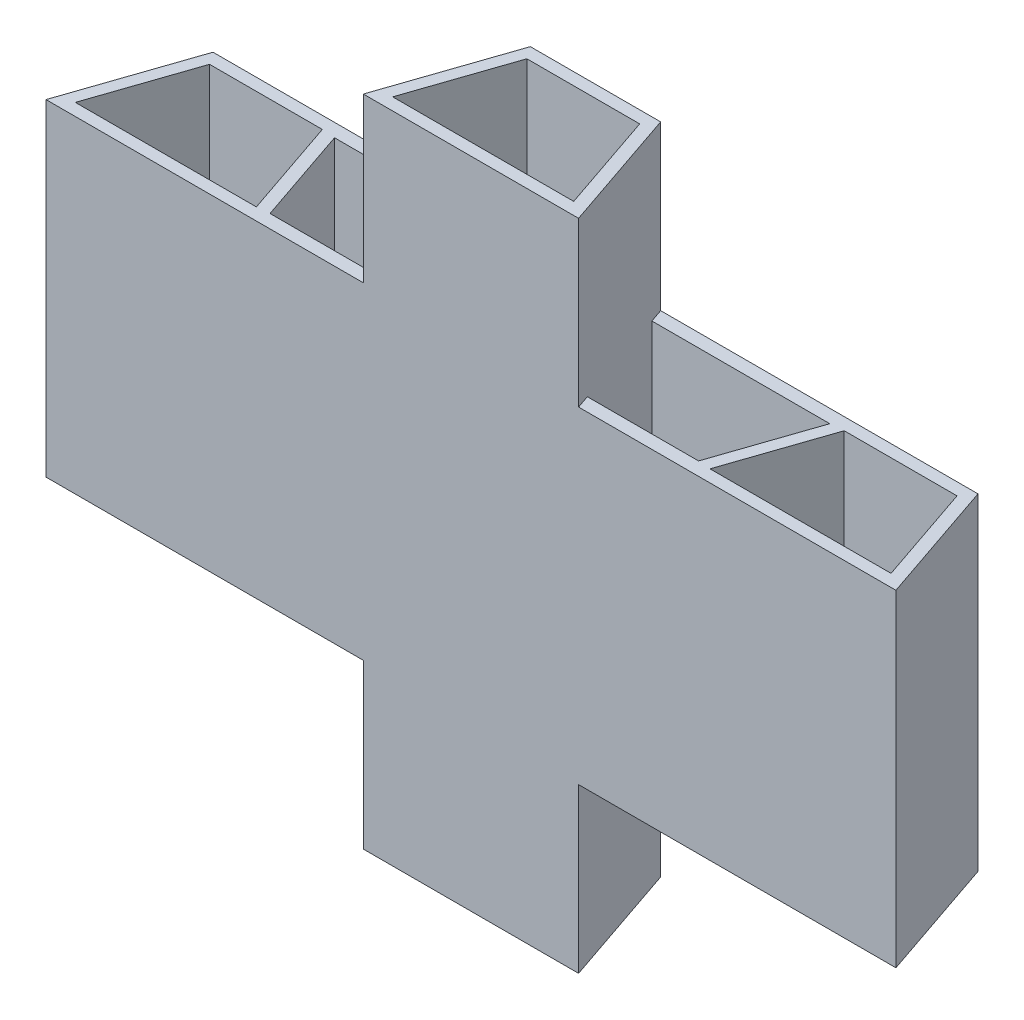
SolidWorks part; units mm, degrees
ref_plane "Front Plane" through (0, 0, 0) normal (0, 0, 1) x (1, 0, 0)
ref_plane "Top Plane" through (0, 0, 0) normal (0, 1, 0) x (1, 0, 0)
ref_plane "Right Plane" through (0, 0, 0) normal (1, 0, 0) x (0, 0, -1)
sketch "Sketch1" plane through (0, 0, 0) normal (0, 1, 0) x (1, 0, 0)
  line L0 (0, 54.8298) -> (0, -49.2445) construction
  line L1 (-104.9814, 0) -> (120.0907, 0) construction
  line L2 (-20, 3) -> (20, 3)
  line L3 (20, 3) -> (12.5, 25)
  line L4 (12.5, 25) -> (-12.5, 25)
  line L5 (-20, 3) -> (-12.5, 25)
  line L6 (15.6695, 25) -> (23.1695, 3)
  line L7 (23.1695, 3) -> (48.1695, 3)
  line L8 (48.1695, 3) -> (55.6695, 25)
  line L9 (55.6695, 25) -> (15.6695, 25)
  line L10 (-48.1695, 3) -> (-55.6695, 25)
  line L11 (-23.1695, 3) -> (-48.1695, 3)
  line L12 (-15.6695, 25) -> (-23.1695, 3)
  line L13 (-55.6695, 25) -> (-15.6695, 25)
  line L14 (58.8391, 25) -> (51.3391, 3)
  line L15 (51.3391, 3) -> (91.3391, 3)
  line L16 (91.3391, 3) -> (83.8391, 25)
  line L17 (83.8391, 25) -> (58.8391, 25)
  line L18 (-91.3391, 3) -> (-83.8391, 25)
  line L19 (-51.3391, 3) -> (-91.3391, 3)
  line L20 (-58.8391, 25) -> (-51.3391, 3)
  line L21 (-83.8391, 25) -> (-58.8391, 25)
  point P10 (0, 3)
  point P11 (0, 25)
  point P27 (-104.9814, 0)
  point P28 (120.0907, 0)
  dimension "D1" = 22
  dimension "D2" = 12.5
  dimension "D3" = 20
  dimension "D4" = 3
  dimension "D5" = 25
  dimension "D6" = 40
  dimension "D7" = 22
  dimension "D8" = 3
  dimension "D9" = 3
  dimension "D10" = 25
  dimension "D11" = 40
  dimension "D12" = 3
  dimension "D13" = 3
  dimension "D14" = 22
sketch "Sketch2" plane through (0, 0, 0) normal (0, 1, 0) x (1, 0, 0)
  line L8 (12.6789, 25.25) -> (-12.6789, 25.25)
  line L9 (-20.3494, 2.75) -> (-12.6789, 25.25)
  line L10 (-20.3494, 2.75) -> (20.3494, 2.75)
  line L11 (20.3494, 2.75) -> (12.6789, 25.25)
  line L12 (24.1923, 0) -> (14.6468, 28)
  line L13 (14.6468, 28) -> (-14.6468, 28)
  line L14 (-24.1923, 0) -> (-14.6468, 28)
  line L15 (-24.1923, 0) -> (24.1923, 0)
extrude "Boss-Extrude1" add sketch "Sketch2" along normal mid plane 147
sketch "Sketch3" plane through (0, 0, 0) normal (0, 1, 0) x (1, 0, 0)
  line L8 (-23.1695, 3) -> (-48.1695, 3) construction
  line L10 (-55.6695, 25) -> (-15.6695, 25) construction
  line L11 (-48.1695, 3) -> (-55.6695, 25) construction
  line L24 (-23.1695, 3) -> (-48.1695, 3)
  line L26 (-55.6695, 25) -> (-15.6695, 25)
  line L27 (-48.1695, 3) -> (-55.6695, 25)
  line L34 (-95.5313, 0) -> (-85.9859, 28)
  line L49 (-85.9859, 28) -> (-14.6468, 28)
  line L50 (-95.5313, 0) -> (-24.1923, 0)
  line L51 (-24.1923, 0) -> (-23.1695, 3)
  line L52 (-58.6602, 25.25) -> (-50.9897, 2.75)
  line L53 (-50.9897, 2.75) -> (-91.6884, 2.75)
  line L54 (-91.6884, 2.75) -> (-84.018, 25.25)
  line L55 (-84.018, 25.25) -> (-58.6602, 25.25)
  line L56 (0, 60.1838) -> (0, -32.4396) construction
  line L57 (0, 54.8298) -> (0, -49.2445) construction
  line L60 (84.018, 25.25) -> (58.6602, 25.25)
  line L61 (91.6884, 2.75) -> (84.018, 25.25)
  line L62 (50.9897, 2.75) -> (91.6884, 2.75)
  line L63 (58.6602, 25.25) -> (50.9897, 2.75)
  line L64 (24.1923, 0) -> (23.1695, 3)
  line L65 (95.5313, 0) -> (24.1923, 0)
  line L66 (85.9859, 28) -> (14.6468, 28)
  line L67 (95.5313, 0) -> (85.9859, 28)
  line L72 (48.1695, 3) -> (55.6695, 25)
  line L73 (55.6695, 25) -> (15.6695, 25)
  line L74 (23.1695, 3) -> (48.1695, 3)
  line L75 (-14.6468, 28) -> (-15.6695, 25)
  line L76 (14.6468, 28) -> (15.6695, 25)
extrude "Boss-Extrude2" add sketch "Sketch3" along normal mid plane 73.5 contours L55 L54 L53 L52 | L60 L63 L62 L61 | L26 L75 L49 L34 L50 L51 L24 L27 | L66 L76 L73 L72 L74 L64 L65 L67
